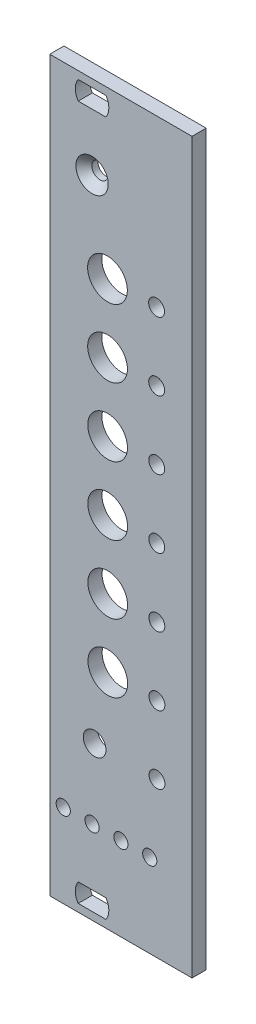
SolidWorks part; units mm, degrees
material "Alliage 1060"
ref_plane "Face" through (0, 0, 0) normal (0, 0, 1) x (1, 0, 0)
ref_plane "Dessus" through (0, 0, 0) normal (0, 1, 0) x (1, 0, 0)
ref_plane "Droite" through (0, 0, 0) normal (1, 0, 0) x (0, 0, -1)
sketch "Model" plane through (0, 0, 0) normal (0, 0, 1) x (1, 0, 0)
  line L0 (0, 128.4) -> (25.06, 128.4)
  line L1 (25.06, 0) -> (0, 0)
  line L2 (9.8954, 123.75) -> (5.0046, 123.75)
  line L3 (5.0046, 127.05) -> (9.8954, 127.05)
  line L4 (9.8954, 1.35) -> (5.0046, 1.35)
  line L5 (5.0046, 4.65) -> (9.8954, 4.65)
  line L6 (0, 0) -> (0, 128.4)
  line L7 (25.06, 128.4) -> (25.06, 0)
  line L8 (7.45, 125.4) -> (7.45, 3) construction
  line L9 (7.45, 4.65) -> (7.45, 1.35) construction
  line L10 (7.45, 127.05) -> (7.45, 123.75) construction
  circle A0 centre (2.37, 14.7) radius 1.25
  circle A1 centre (12.53, 14.7) radius 1.25
  circle A3 centre (7.45, 14.7) radius 1.25
  arc A4 (5.0046, 4.65) -> (5.0046, 1.35) centre (7.45, 3) ccw
  circle A5 centre (7.45, 113.7) radius 1.45
  arc A6 (5.0046, 127.05) -> (5.0046, 123.75) centre (7.45, 125.4) ccw
  arc A7 (9.8954, 1.35) -> (9.8954, 4.65) centre (7.45, 3) ccw
  arc A8 (9.8954, 123.75) -> (9.8954, 127.05) centre (7.45, 125.4) ccw
  circle A9 centre (17.61, 14.7) radius 1.25
  point P28 (7.45, 3)
  point P31 (7.45, 125.4)
  dimension "D3" = 2.9
  dimension "D4" = 2.5
  dimension "D5" = 5.08
  dimension "D10" = 2.95
  dimension "D15" = 2.95
  dimension "D1" = 128.4
  dimension "D2" = 25.06
  dimension "D6" = 5.08
  dimension "D7" = 5.08
  dimension "D8" = 3
  dimension "D9" = 14.7
  dimension "D11" = 99
  dimension "D12" = 7.45
  dimension "D13" = 3.3
  dimension "D14" = 3
  dimension "D16" = 3.3
extrude "Boss.-Extru.1" add sketch "Model" along normal blind 2.5
chamfer "Chanfrein1" distance 1.4 angle 45 1 edges at (8.9, 113.7, 2.5)
sketch "Esquisse1" plane through (0, 0, 2.5) normal (0, 0, 1) x (1, 0, 0)
  circle A0 centre (18.8146, 99.2115) radius 1.4
  circle A1 centre (18.8268, 87.2115) radius 1.4
  circle A2 centre (18.8389, 75.2115) radius 1.4
  circle A3 centre (18.851, 63.2115) radius 1.4
  circle A4 centre (18.8631, 51.2115) radius 1.4
  circle A5 centre (18.8752, 39.2116) radius 1.4
  circle A6 centre (18.8874, 27.2116) radius 1.4
  circle A7 centre (10.1646, 99.2028) radius 3.5
  circle A8 centre (10.1768, 87.2028) radius 3.5
  circle A9 centre (10.1889, 75.2028) radius 3.5
  circle A10 centre (10.201, 63.2028) radius 3.5
  circle A11 centre (10.2131, 51.2028) radius 3.5
  circle A12 centre (10.2253, 39.2028) radius 3.5
  circle A13 centre (7.9006, 27.2005) radius 2
  dimension "D1" = 2.8
  dimension "D2" = 2.8
  dimension "D3" = 2.8
  dimension "D4" = 2.8
  dimension "D5" = 2.8
  dimension "D6" = 2.8
  dimension "D7" = 2.8
  dimension "D8" = 7
  dimension "D9" = 7
  dimension "D10" = 7
  dimension "D11" = 7
  dimension "D12" = 7
  dimension "D13" = 7
  dimension "D14" = 4
extrude "Enlèv. mat.-Extru.1" cut sketch "Esquisse1" against normal through all
